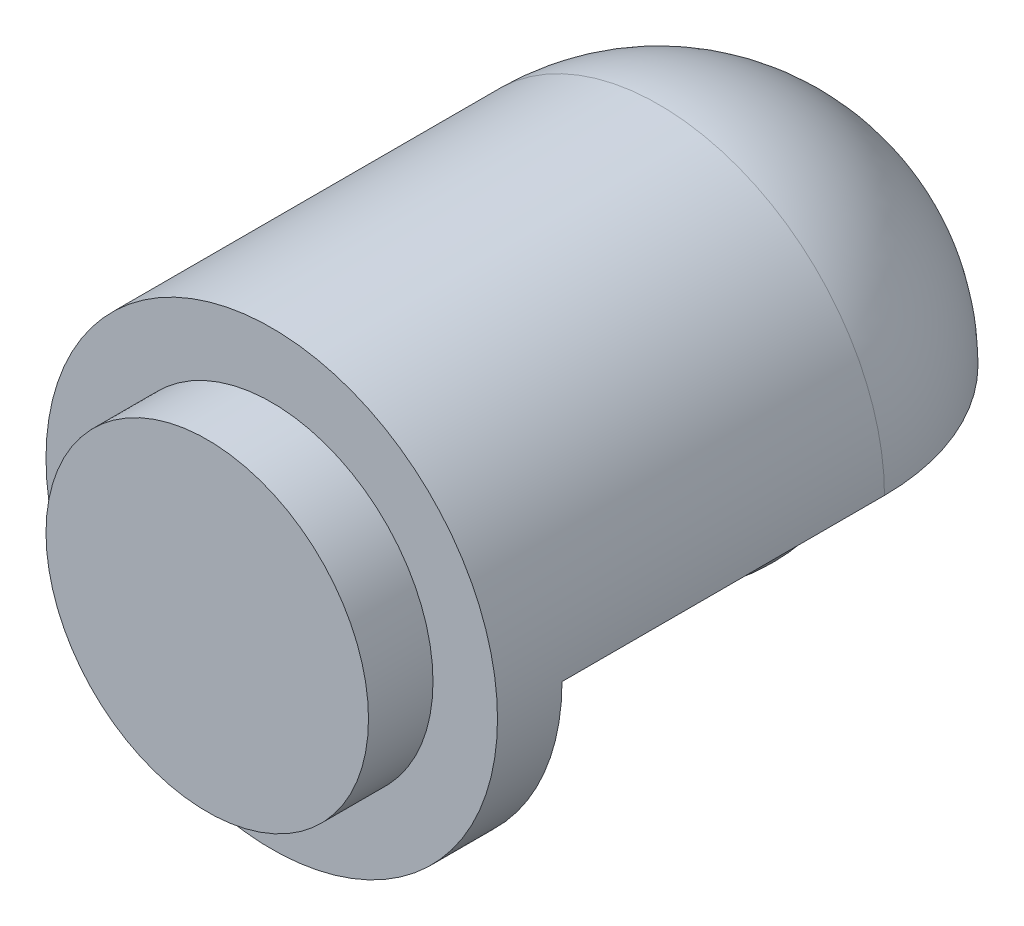
SolidWorks part; units mm, degrees
ref_plane "Front Plane" through (0, 0, 0) normal (0, 0, 1) x (1, 0, 0)
ref_plane "Top Plane" through (0, 0, 0) normal (0, 1, 0) x (1, 0, 0)
ref_plane "Right Plane" through (0, 0, 0) normal (1, 0, 0) x (0, 0, -1)
sketch "Sketch1" plane through (0, 0, 0) normal (0, 1, 0) x (1, 0, 0)
  line L0 (0, 50) -> (0, -50)
  arc A0 (0, 50) -> (0, -50) centre (0, 0) ccw
  dimension "D1" = 100
revolve "Revolve1" add sketch "Sketch1" angle 360 about L0
sketch "Sketch2" plane through (0, 0, 0) normal (0, 1, 0) x (1, 0, 0)
  line L0 (0, 70) -> (0, -120)
  line L1 (-70, 0) -> (0, 0)
  line L2 (-70, 0) -> (-70, -120)
  line L3 (-70, -120) -> (0, -120)
  arc A0 (0, 70) -> (-70, 0) centre (0, 0) ccw
  dimension "D1" = 140
  dimension "D2" = 120
revolve "Revolve2" add sketch "Sketch2" angle 180 about L0
sketch "Sketch3" plane through (0, 0, 120) normal (0, 0, 1) x (1, 0, 0)
  circle A0 centre (0, 0) radius 50
extrude "Boss-Extrude1" add sketch "Sketch3" along normal blind 20 contours A0
sketch "Sketch4" plane through (0, 0, 120) normal (0, 0, 1) x (1, 0, 0)
  circle A0 centre (0, 0) radius 70
extrude "Boss-Extrude2" add sketch "Sketch4" against normal blind 20 contours A0
